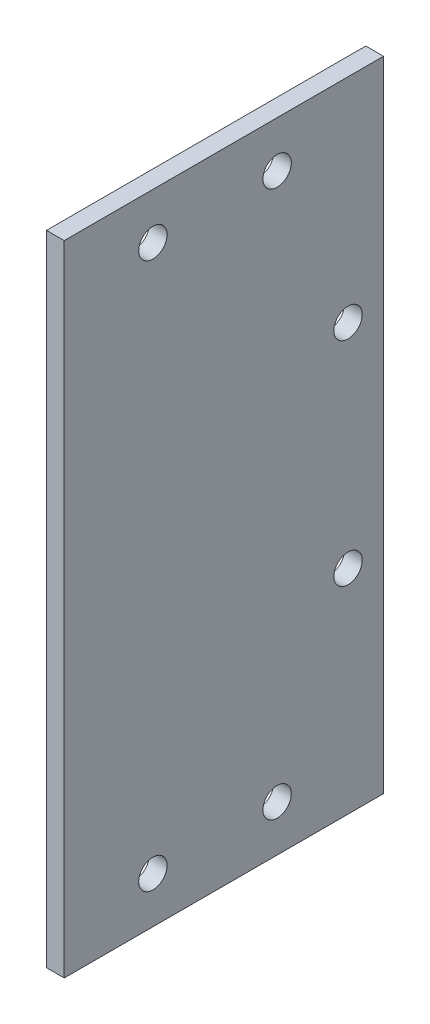
SolidWorks part; units mm, degrees
ref_plane "Front Plane" through (0, 0, 0) normal (1, 0, 0) x (0, 1, 0)
ref_plane "Top Plane" through (0, 0, 0) normal (0, 0, 1) x (0, 1, 0)
ref_plane "Right Plane" through (0, 0, 0) normal (0, 1, 0) x (-1, 0, 0)
sketch "Sketch1" plane through (0, 0, 0) normal (1, 0, 0) x (0, 1, 0)
  line L0 (0, -55) -> (0, 55) construction
  line L1 (-90, 45) -> (90, 45)
  line L2 (-90, 45) -> (-90, -45)
  line L3 (-90, -45) -> (90, -45)
  line L4 (90, 45) -> (90, -45)
  line L5 (-90, 45) -> (90, -45) construction
  line L6 (-90, -45) -> (90, 45) construction
  circle A0 centre (-77, 20) radius 4
  circle A1 centre (-77, -15) radius 4
  circle A2 centre (-30, -35) radius 4
  circle A3 centre (30, -35) radius 4
  circle A4 centre (77, -15) radius 4
  circle A5 centre (77, 20) radius 4
  point P0 (0, 0)
  dimension "D3" = 8
  dimension "D1" = 90
  dimension "D2" = 180
  dimension "D4" = 35
  dimension "D5" = 30
  dimension "D6" = 13
  dimension "D7" = 47
  dimension "D8" = 10
extrude "Boss-Extrude1" add sketch "Sketch1" along normal blind 5
